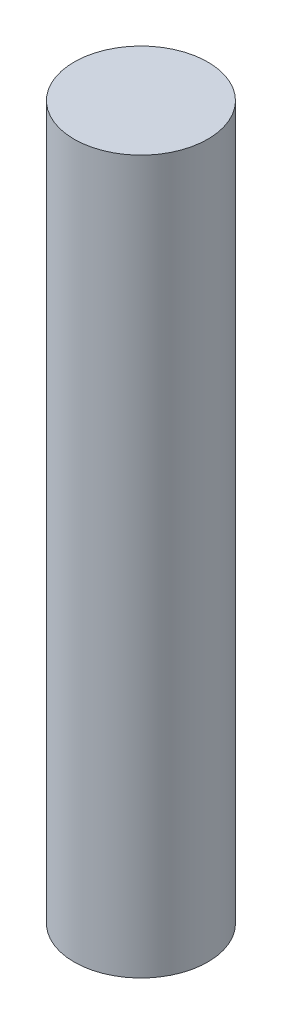
SolidWorks part; units mm, degrees
ref_plane "Front Plane" through (0, 0, 0) normal (0, 0, 1) x (1, 0, 0)
ref_plane "Top Plane" through (0, 0, 0) normal (0, 1, 0) x (1, 0, 0)
ref_plane "Right Plane" through (0, 0, 0) normal (1, 0, 0) x (0, 0, -1)
sketch "Sketch1" plane through (0, 0, 0) normal (0, 1, 0) x (1, 0, 0)
  circle A0 centre (0, 0) radius 4.6913
extrude "Boss-Extrude1" add sketch "Sketch1" along normal blind 50 contours A0
